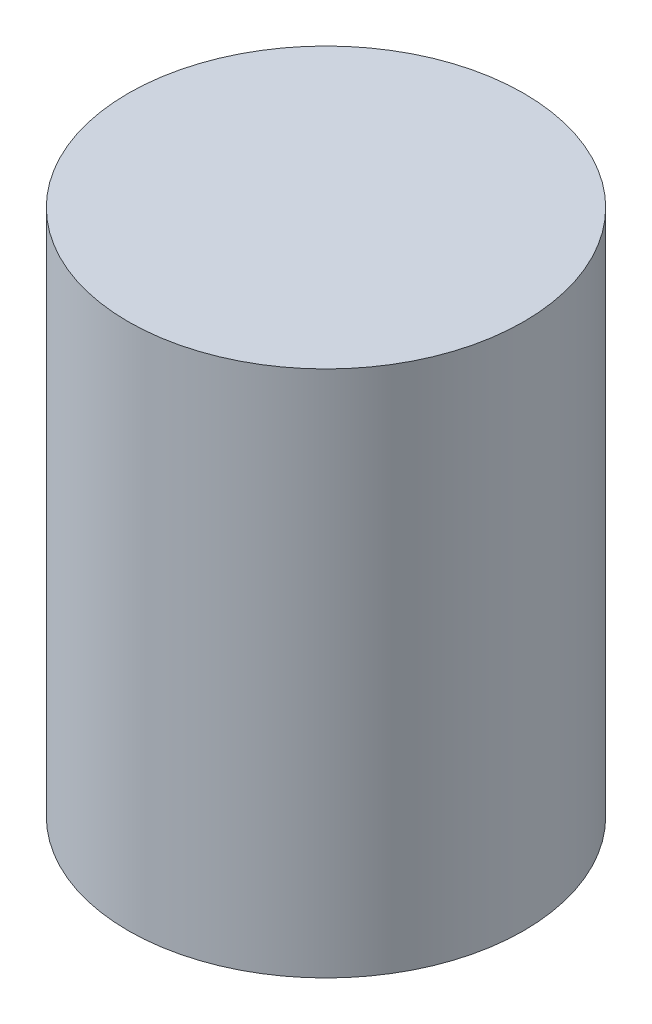
SolidWorks part; units mm, degrees
ref_plane "정면" through (0, 0, 0) normal (0, 0, 1) x (1, 0, 0)
ref_plane "윗면" through (0, 0, 0) normal (0, 1, 0) x (1, 0, 0)
ref_plane "우측면" through (0, 0, 0) normal (1, 0, 0) x (0, 0, -1)
sketch "스케치1" plane through (0, 0, 0) normal (0, 0, 1) x (1, 0, 0)
  line L0 (4.7625, 12.7) -> (0, 12.7)
  line L1 (0, 12.7) -> (0, 0)
  line L2 (0, 0) -> (4.7625, 0)
  line L3 (4.7625, 0) -> (4.7625, 12.7)
  line L4 (0, 12.7) -> (0, 0) construction
  dimension "D1" = 12.7
  dimension "D2" = 4.7625
revolve "회전1" add sketch "스케치1" angle 360 about L4
